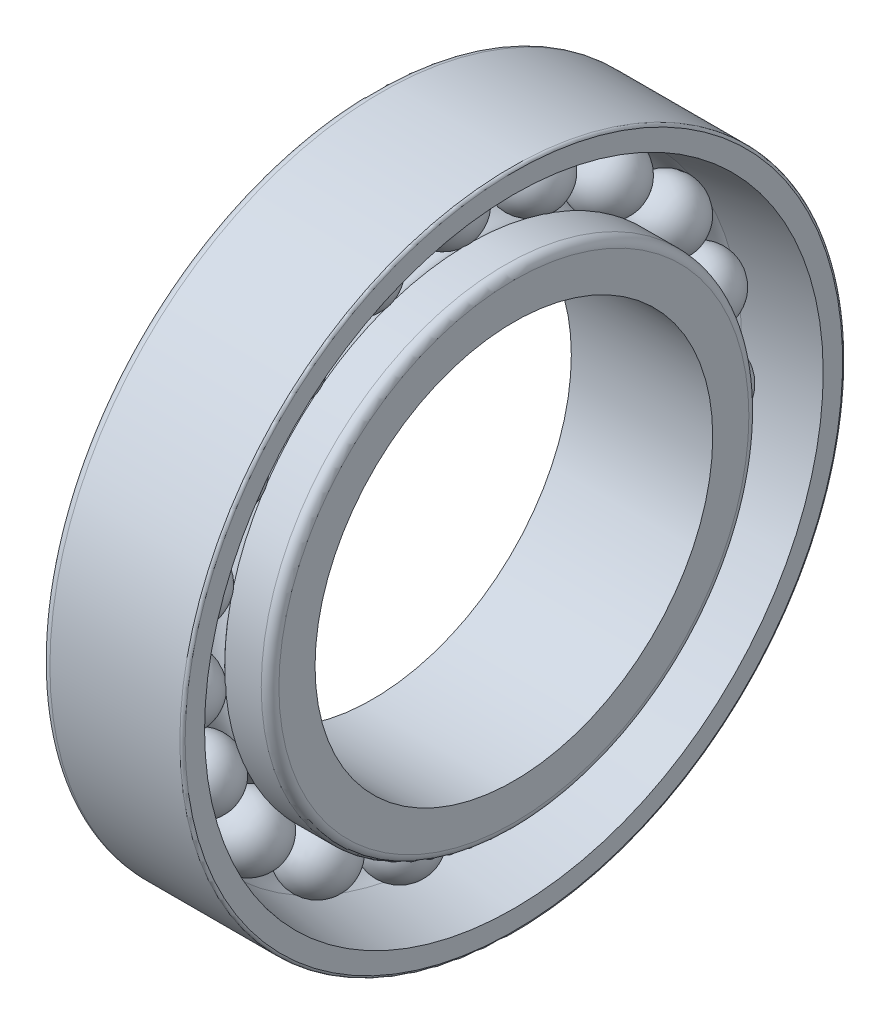
SolidWorks part; units mm, degrees
material "GCr15"
ref_plane "前视" through (0, 0, 0) normal (0, 0, 1) x (1, 0, 0)
ref_plane "上视" through (0, 0, 0) normal (0, 1, 0) x (1, 0, 0)
ref_plane "右视" through (0, 0, 0) normal (1, 0, 0) x (0, 0, -1)
sketch "尺寸草图" plane through (0, 0, 0) normal (0, 0, 1) x (1, 0, 0)
  line L0 (-3.205, -4.1476) -> (71.795, -4.1476)
  point P2 (41.795, -4.1476)
  point P3 (25.795, -4.1476)
  point P4 (0.7517, -4.1476)
  point P7 (71.495, -4.1476)
  point P8 (70.795, -4.1476)
  dimension "DD" = 75
  dimension "d" = 45
  dimension "B" = 16
  dimension "r1" = 0.3
  dimension "r" = 1
sketch "草图1" plane through (0, 0, 0) normal (0, 0, 1) x (1, 0, 0)
  line L0 (0, 0) -> (106.1418, 0) construction
  line L1 (0, 0) -> (0, 122.9209) construction
  line L2 (0, 37.5) -> (16, 37.5)
  line L3 (0, 22.5) -> (16, 22.5)
  line L4 (0, 37.5) -> (0, 22.5)
  line L5 (16, 37.5) -> (16, 27.5895)
  line L6 (16, 22.5) -> (16, 27.5895)
  line L7 (16, 27.5895) -> (0, 27.5895)
  line L9 (0, 30) -> (95.9613, 30) construction
  line L10 (8, 0) -> (8, 122.9209) construction
  line L11 (8, 33.75) -> (15, 33.75)
  line L12 (5.1273, 32.4105) -> (0, 32.4105)
  line L13 (15, 33.75) -> (15, 35)
  line L14 (15, 35) -> (16, 35)
  line L15 (8, 30) -> (5.1273, 32.4105) construction
  circle A0 centre (8, 30) radius 3.75
  dimension "D1" = 16
  dimension "D2" = 8
  dimension "D4" = 45
  dimension "D5" = 75
  dimension "D6" = 16
  dimension "D9" = 5
  dimension "D10" = 1
  dimension "D3" = 50
  dimension "D8" = 3.75
sketch "草图2" plane through (0, 0, 0) normal (0, 0, 1) x (1, 0, 0)
  line L0 (15, 33.75) -> (15, 35) construction
  line L1 (15, 35) -> (16, 35) construction
  line L2 (0, 37.5) -> (16, 37.5) construction
  line L3 (8, 33.75) -> (15, 33.75) construction
  line L4 (5.1273, 32.4105) -> (0, 32.4105) construction
  line L5 (0, 0) -> (106.1418, 0) construction
  line L6 (15, 33.75) -> (15, 35) construction
  line L7 (15, 35) -> (16, 35) construction
  line L8 (0, 37.5) -> (16, 37.5)
  line L9 (8, 33.75) -> (15, 33.75) construction
  line L10 (5.1273, 32.4105) -> (0, 32.4105)
  line L11 (0, 0) -> (106.1418, 0) construction
  line L12 (16, 37.5) -> (16, 27.5895) construction
  line L13 (0, 37.5) -> (0, 22.5) construction
  line L14 (16, 37.5) -> (16, 35)
  line L15 (0, 37.5) -> (0, 32.4105)
  line L16 (16, 35) -> (8, 33.75)
  circle A0 centre (8, 30) radius 3.75 construction
  arc A1 (8, 33.75) -> (5.1273, 32.4105) centre (8, 30) ccw
revolve "基体-旋转" add sketch "草图2" angle 360 about L11
sketch "草图3" plane through (0, 0, 0) normal (0, 0, 1) x (1, 0, 0)
  line L0 (0, 30) -> (95.9613, 30) construction
  line L1 (0, 30) -> (95.9613, 30) construction
  line L2 (11.8, 30) -> (4.2, 30)
  arc A0 (11.8, 30) -> (4.2, 30) centre (8, 30) ccw
  circle A1 centre (8, 30) radius 3.75
  arc A2 (11.75, 30) -> (4.25, 30) centre (8, 30) ccw construction
  dimension "D1" = 0
  dimension "D2" = 0.05
revolve "凸台-旋转1" add sketch "草图3" angle 360 about L1
sketch "草图4" plane through (0, 0, 0) normal (0, 0, 1) x (1, 0, 0)
  line L0 (16, 22.5) -> (16, 27.5895) construction
  line L1 (0, 37.5) -> (0, 22.5) construction
  line L2 (0, 22.5) -> (16, 22.5) construction
  line L3 (16, 27.5895) -> (0, 27.5895) construction
  line L4 (16, 22.5) -> (16, 27.5895)
  line L5 (5.1273, 27.5895) -> (0, 27.5895)
  line L6 (0, 22.5) -> (16, 22.5)
  line L7 (16, 27.5895) -> (10.8727, 27.5895)
  line L8 (0, 0) -> (106.1418, 0) construction
  line L9 (0, 0) -> (106.1418, 0) construction
  line L11 (0, 27.5895) -> (0, 22.5)
  circle A0 centre (8, 30) radius 3.75 construction
  arc A1 (5.1273, 27.5895) -> (10.8727, 27.5895) centre (8, 30) ccw
revolve "凸台-旋转2" add sketch "草图4" angle 360 about L9
fillet "圆角1" radius 0.3 1 edges at (16, 0, 37.5)
fillet "圆角2" radius 1 2 edges at (16, 0, 27.5895) (0, 0, 37.5)
pattern_circular "阵列(圆周)2" count 19 over 360 about axis through (0, 0, 0) along (1, 0, 0) of "凸台-旋转1"
equation "\"D5@草图1\" = \"DD@尺寸草图\""
equation "\"D6@草图1\" = \"B@尺寸草图\""
equation "\"D1@圆角2\" = \"r@尺寸草图\""
equation "\"D1@圆角1\" = \"r1@尺寸草图\""
equation "\"D4@草图1\" = \"d@尺寸草图\""
equation "\"D1@阵列(圆周)2\" =3.14* (  \"DD@尺寸草图\" + \"d@尺寸草图\" )  / 2/ (  ( \"DD@尺寸草图\" - \"d@尺寸草图\" )  / 3 ) "
equation "\"D1@草图1\" = \"D6@草图1\""
equation "\"D2@草图1\" = \"D1@草图1\" / 2"
equation "\"D9@草图1\" =   ( \"D5@草图1\" - \"D4@草图1\" )  /6"
equation "\"D8@草图1\" =  ( \"D5@草图1\" - \"D4@草图1\" )  / 8"
